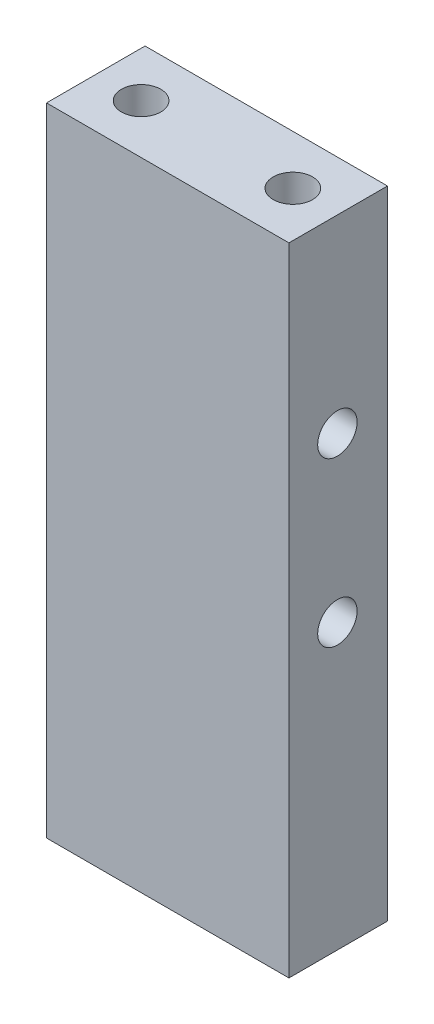
SolidWorks part; units mm, degrees
ref_plane "Front Plane" through (0, 0, 0) normal (0, 0, 1) x (1, 0, 0)
ref_plane "Top Plane" through (0, 0, 0) normal (0, 1, 0) x (1, 0, 0)
ref_plane "Right Plane" through (0, 0, 0) normal (1, 0, 0) x (0, 0, -1)
other "Graphic1"
ref_plane "Plane1" through (0, 0, 6) normal (0, 0, 1) x (1, 0, 0)
sketch "Sketch1" plane through (0, 0, 6) normal (0, 0, 1) x (1, 0, 0)
  line L1 (-246.4266, 284.5112) -> (-234.1266, 284.5112)
  line L2 (-246.4266, 284.5112) -> (-246.4266, 252.2112)
  line L3 (-246.4266, 252.2112) -> (-234.1266, 252.2112)
  line L4 (-234.1266, 284.5112) -> (-234.1266, 252.2112)
  dimension "D1" = 12.3
  dimension "D2" = 32.3
extrude "Boss-Extrude1" add sketch "Sketch1" along normal blind 5
sketch "Sketch3" plane through (-246.4266, 0, 0) normal (-1, 0, 0) x (0, 0, 1)
  line L0 (11, 284.5112) -> (6, 284.5112) construction
  circle A0 centre (8.5422, 274.9112) radius 1
  circle A1 centre (8.5422, 266.6112) radius 1
  dimension "D1" = 2
  dimension "D3" = 2
  dimension "D2" = 9.6
  dimension "D4" = 8.3
extrude "Cut-Extrude1" cut sketch "Sketch3" against normal through all
sketch "Sketch4" plane through (0, 252.2112, 0) normal (0, -1, 0) x (-1, 0, 0)
  line L0 (234.1266, -11) -> (234.1266, -6) construction
  line L2 (-12.101, -6) -> (12.101, -6) construction
  circle A0 centre (244.1266, -8.5) radius 1
  circle A1 centre (236.4266, -8.5) radius 1
  dimension "D1" = 7.7
  dimension "D2" = 2.3
  dimension "D3" = 2.5
extrude "Cut-Extrude2" cut sketch "Sketch4" against normal through all
